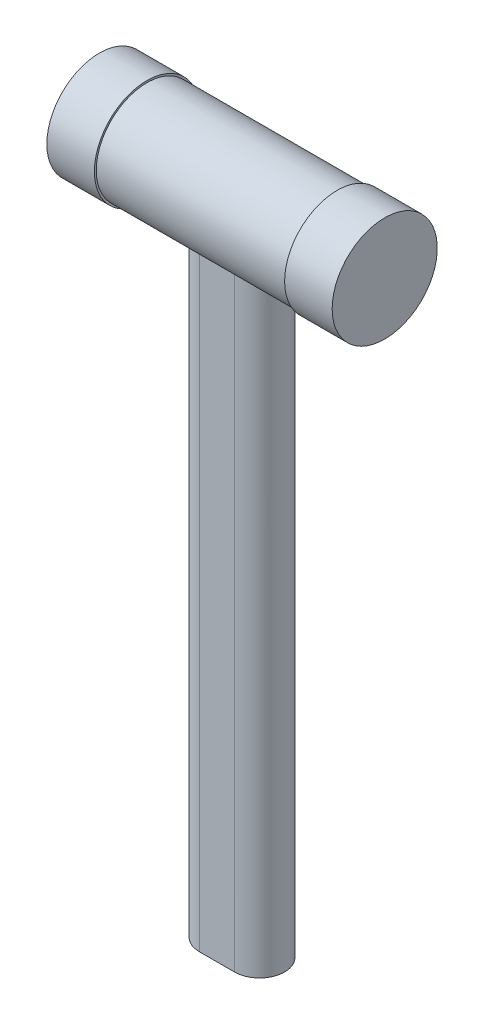
SolidWorks part; units mm, degrees
material "AISI Type A2 Werkzeugstahl"
ref_plane "Vorne" through (0, 0, 0) normal (0, 0, 1) x (1, 0, 0)
ref_plane "Oben" through (0, 0, 0) normal (0, 1, 0) x (1, 0, 0)
ref_plane "Rechts" through (0, 0, 0) normal (1, 0, 0) x (0, 0, -1)
sketch "Skizze1" plane through (0, 0, 0) normal (0, 0, 1) x (1, 0, 0)
  line L0 (-67.2475, 0) -> (78.328, 0) construction
  line L1 (-57, 0) -> (-57, 21)
  line L2 (-57, 21) -> (-38, 21)
  line L3 (-38, 21) -> (-38, 0)
  line L4 (-38, 20.25) -> (38, 20.25)
  line L5 (38, 21) -> (38, 0)
  line L6 (38, 21) -> (57, 21)
  line L7 (57, 21) -> (57, 0)
  line L8 (-57, 0) -> (57, 0)
  line L9 (0, 52.3095) -> (0, -9.2395) construction
  dimension "D1" = 76
  dimension "D2" = 42
  dimension "D3" = 40.5
  dimension "D4" = 19
revolve "Rotation1" add sketch "Skizze1" angle 360 about L0
sketch "Skizze2" plane through (0, 0, 0) normal (0, 1, 0) x (1, 0, 0)
  line L0 (-7, 0) -> (7, 0) construction
  line L1 (-7, 10) -> (7, 10)
  line L2 (-7, -10) -> (7, -10)
  arc A0 (-7, 10) -> (-7, -10) centre (-7, 0) ccw
  arc A1 (7, -10) -> (7, 10) centre (7, 0) ccw
  point P3 (0, 0)
  dimension "D1" = 20
  dimension "D2" = 14
extrude "Aufsatz-Linear austragen1" add sketch "Skizze2" against normal blind 260
